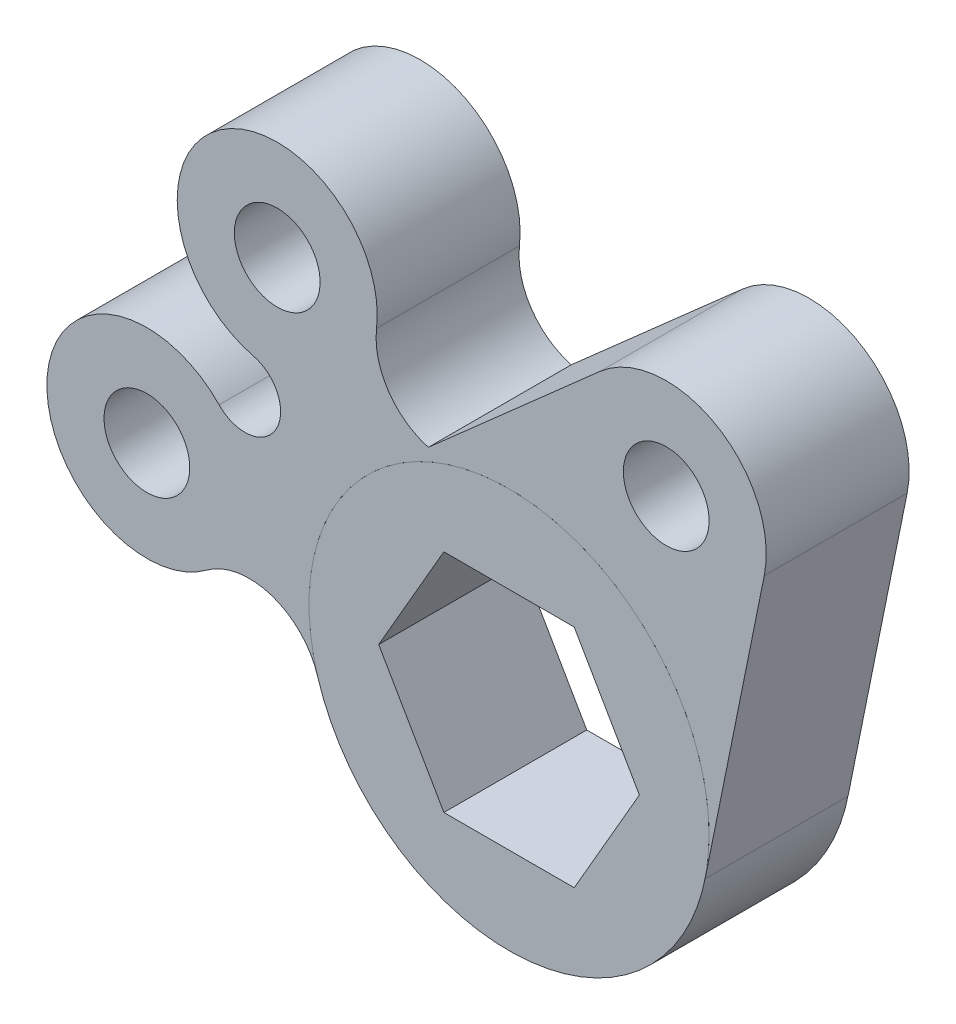
SolidWorks part; units mm, degrees
ref_plane "Front" through (0, 0, 0) normal (0, 0, 1) x (1, 0, 0)
ref_plane "Top" through (0, 0, 0) normal (0, 1, 0) x (1, 0, 0)
ref_plane "Right" through (0, 0, 0) normal (1, 0, 0) x (0, 0, -1)
sketch "Эскиз1" plane through (0, 0, 0) normal (0, 0, 1) x (1, 0, 0)
  line L1 (2.2805, -3.95) -> (4.5611, 0)
  line L2 (4.5611, 0) -> (2.2805, 3.95)
  line L3 (2.2805, 3.95) -> (-2.2805, 3.95)
  line L4 (-2.2805, 3.95) -> (-4.5611, 0)
  line L5 (-4.5611, 0) -> (-2.2805, -3.95)
  line L6 (-2.2805, -3.95) -> (2.2805, -3.95)
  circle A0 centre (0, 0) radius 3.95 construction
  circle A1 centre (0, 0) radius 7
  dimension "D2" = 14
  dimension "D1" = 7.9
extrude "Бобышка-Вытянуть1" add sketch "Эскиз1" along normal blind 5
sketch "Эскиз2" plane through (0, 0, 0) normal (0, 0, -1) x (-1, 0, 0)
  line L0 (-8.9304, 8.8317) -> (-6.8608, -1.3892)
  line L1 (-3.1833, 12.1498) -> (4.6335, 5.247)
  line L2 (-2.2805, 3.95) -> (10.6768, 11.4309) construction
  line L3 (2.2805, -3.95) -> (12.4852, 1.9417) construction
  line L4 (2.2805, 3.95) -> (4.5611, 0) construction
  line L5 (8.1118, 9.95) -> (12.6728, 2.05) construction
  circle A0 centre (-5.5, 9.5263) radius 1.5
  circle A1 centre (12.6728, 2.05) radius 1.5
  circle A2 centre (8.1118, 9.95) radius 1.5
  circle A3 centre (12.6728, 2.05) radius 3.5
  circle A4 centre (8.1118, 9.95) radius 3.5
  circle A5 centre (-5.5, 9.5263) radius 3.5
  circle A6 centre (0, 0) radius 7 construction
  circle A7 centre (9.0895, -2.7624) radius 2.5
  circle A8 centre (9.2437, 5.3368) radius 1.25
  circle A9 centre (2.1524, 9.253) radius 2.5
  circle M6 centre (0, 0) radius 7
  dimension "D1" = 3
  dimension "D2" = 7
  dimension "D4" = 5
  dimension "D5" = 2.5
  dimension "D3" = 12
extrude "Бобышка-Вытянуть4" add sketch "Эскиз2" against normal blind 5 separate body contours A9 A4 L1 M6 | A4 L1 A2 M6 | A3 A1 M6 | A7 A3 M6 | A9 L1 A5 L0 M6 | A5 A0 | L1 A4 M6
